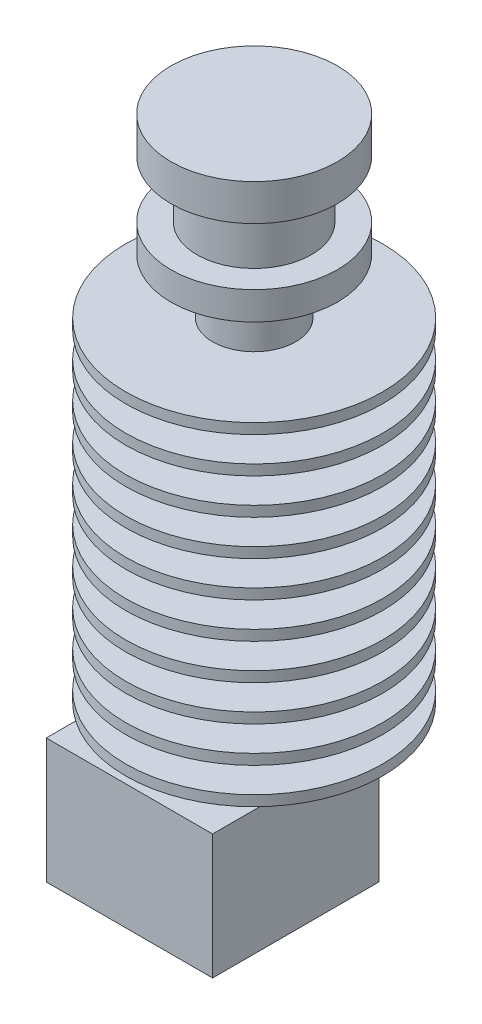
SolidWorks part; units mm, degrees
material "Liga 1060"
ref_plane "Plano frontal" through (0, 0, 0) normal (0, 0, 1) x (1, 0, 0)
ref_plane "Plano superior" through (0, 0, 0) normal (0, 1, 0) x (1, 0, 0)
ref_plane "Plano direito" through (0, 0, 0) normal (1, 0, 0) x (0, 0, -1)
sketch "Esboço1" plane through (0, 0, 0) normal (0, 0, 1) x (1, 0, 0)
  line L0 (0, 51.6592) -> (0, 1.6592)
  line L1 (0, 51.6592) -> (8, 51.6592)
  line L2 (8, 51.6592) -> (8, 48.1592)
  line L3 (5.5, 48.1592) -> (5.5, 42.6592)
  line L4 (5.5, 42.6592) -> (8, 42.6592)
  line L5 (8, 42.6592) -> (8, 39.9592)
  line L6 (8, 39.9592) -> (4, 39.9592)
  line L7 (5.5, 48.1592) -> (8, 48.1592)
  line L8 (4, 39.9592) -> (4, 34.6592)
  line L9 (4, 34.6592) -> (12.35, 34.6592)
  line L10 (12.35, 34.6592) -> (12.35, 33.6592)
  line L11 (12.35, 2.6592) -> (2, 2.6592)
  line L12 (2, 2.6592) -> (0, 2.6592) construction
  line L13 (2, 2.6592) -> (2, 1.6592)
  line L14 (2, 1.6592) -> (0, 1.6592)
  line L15 (0, 51.6592) -> (0, 1.6592) construction
  line L16 (12.35, 33.6592) -> (4, 33.6592)
  line L17 (4, 33.6592) -> (4, 31.2148)
  line L18 (4, 31.2148) -> (12.35, 31.2148)
  line L19 (12.35, 31.2148) -> (12.35, 30.2148)
  line L20 (12.35, 30.2148) -> (4, 30.2148)
  line L21 (4, 30.2148) -> (4, 27.7703)
  line L22 (4, 27.7703) -> (12.35, 27.7703)
  line L23 (12.35, 27.7703) -> (12.35, 26.7703)
  line L24 (12.35, 26.7703) -> (4, 26.7703)
  line L25 (4, 26.7703) -> (4, 24.3259)
  line L26 (4, 24.3259) -> (12.35, 24.3259)
  line L27 (12.35, 24.3259) -> (12.35, 23.3259)
  line L28 (12.35, 23.3259) -> (4, 23.3259)
  line L29 (4, 23.3259) -> (4, 20.8815)
  line L30 (4, 20.8815) -> (12.35, 20.8815)
  line L31 (12.35, 20.8815) -> (12.35, 19.8815)
  line L32 (12.35, 19.8815) -> (4, 19.8815)
  line L33 (4, 19.8815) -> (4, 17.437)
  line L34 (4, 17.437) -> (12.35, 17.437)
  line L35 (12.35, 17.437) -> (12.35, 16.437)
  line L36 (12.35, 16.437) -> (4, 16.437)
  line L37 (4, 16.437) -> (4, 13.9926)
  line L38 (4, 13.9926) -> (12.35, 13.9926)
  line L39 (12.35, 13.9926) -> (12.35, 12.9926)
  line L40 (12.35, 12.9926) -> (4, 12.9926)
  line L41 (4, 12.9926) -> (4, 10.5481)
  line L42 (4, 10.5481) -> (12.35, 10.5481)
  line L43 (12.35, 10.5481) -> (12.35, 9.5481)
  line L44 (12.35, 9.5481) -> (4, 9.5481)
  line L45 (4, 9.5481) -> (4, 7.1037)
  line L46 (4, 7.1037) -> (12.35, 7.1037)
  line L47 (12.35, 7.1037) -> (12.35, 6.1037)
  line L48 (12.35, 6.1037) -> (4, 6.1037)
  line L49 (4, 6.1037) -> (4, 3.6592)
  line L50 (4, 3.6592) -> (12.35, 3.6592)
  line L51 (12.35, 3.6592) -> (12.35, 2.6592)
  line L55 (4, 2.6592) -> (4, 0.2148) [skipped]
  line L56 (4, 0.2148) -> (12.35, 0.2148) [skipped]
  line L57 (12.35, 2.6592) -> (4, 2.6592) [skipped]
  dimension "D1" = 32
  dimension "D2" = 3.5
  dimension "D3" = 5.5
  dimension "D4" = 2.7
  dimension "D5" = 1
  dimension "D6" = 50
  dimension "D7" = 4
  dimension "D8" = 24.7
  dimension "D9" = 1
  dimension "D11" = 1
  dimension "D10" = 10
revolve "Revolução1" add sketch "Esboço1" angle 360 about L15
sketch "Esboço3" plane through (0, 1.6592, 0) normal (0, -1, 0) x (1, 0, 0)
  line L0 (0, 0) -> (0, 4) construction
  line L2 (-8, 12) -> (8, 12)
  line L3 (-8, 12) -> (-8, -4)
  line L4 (-8, -4) -> (8, -4)
  line L5 (8, 12) -> (8, -4)
  line L6 (-8, 12) -> (8, -4) construction
  line L7 (-8, -4) -> (8, 12) construction
extrude "Ressalto-extrusão1" add sketch "Esboço3" along normal blind 12
sketch "Esboço4" plane through (0, -10.3408, 0) normal (0, -1, 0) x (1, 0, 0)
  circle A0 centre (0, 0) radius 3
extrude "Ressalto-extrusão2" add sketch "Esboço4" along normal blind 5 draft 26
